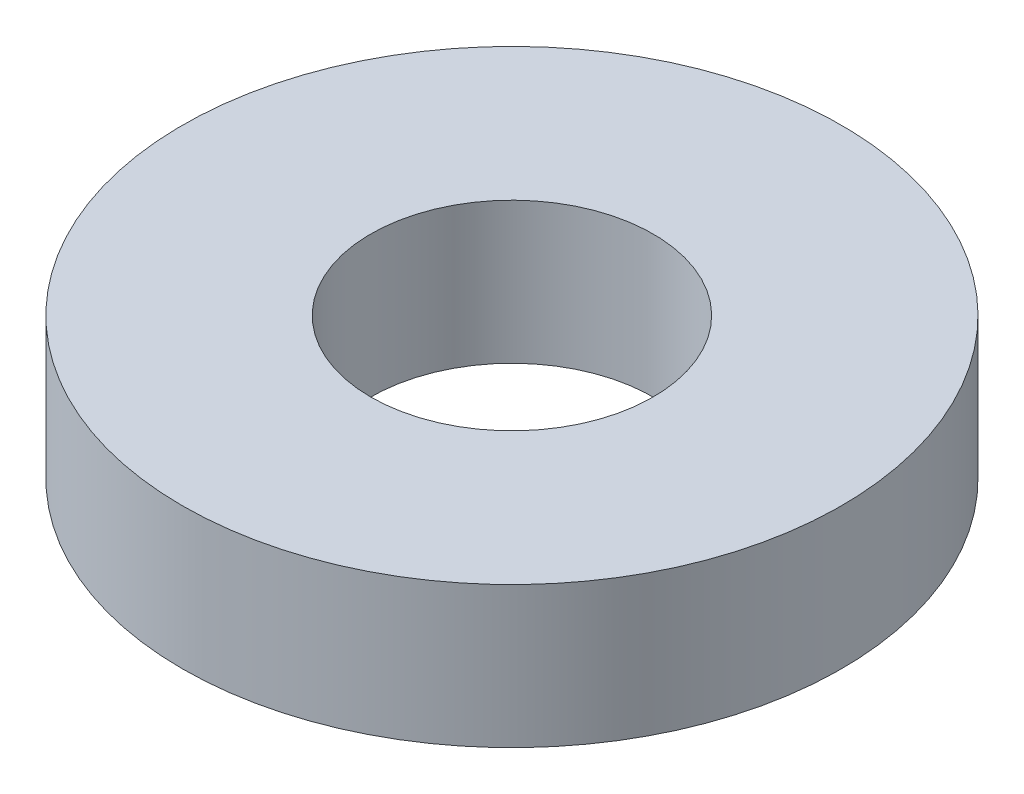
SolidWorks part; units mm, degrees
ref_plane "Front Plane" through (0, 0, 0) normal (0, 0, 1) x (1, 0, 0)
ref_plane "Top Plane" through (0, 0, 0) normal (0, 1, 0) x (1, 0, 0)
ref_plane "Right Plane" through (0, 0, 0) normal (1, 0, 0) x (0, 0, -1)
sketch "Sketch1" plane through (0, 0, 0) normal (0, 1, 0) x (1, 0, 0)
  circle A0 centre (0, 0) radius 3
  circle A1 centre (0, 0) radius 7
  dimension "D1" = 6
  dimension "D2" = 14
extrude "Boss-Extrude1" add sketch "Sketch1" along normal blind 3
